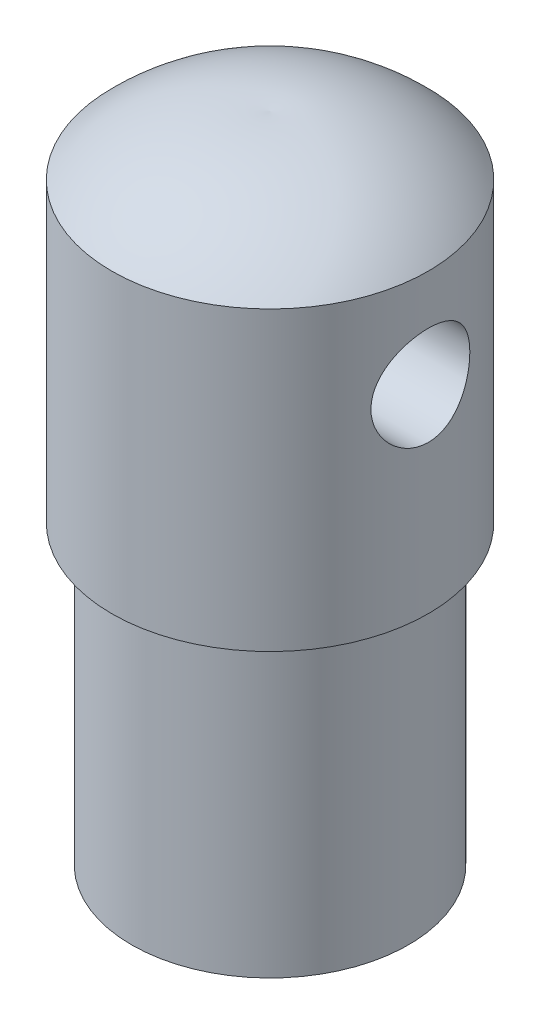
SolidWorks part; units mm, degrees
material "ABS PC"
ref_plane "Front Plane" through (0, 0, 0) normal (0, 0, 1) x (1, 0, 0)
ref_plane "Top Plane" through (0, 0, 0) normal (0, 1, 0) x (1, 0, 0)
ref_plane "Right Plane" through (0, 0, 0) normal (1, 0, 0) x (0, 0, -1)
sketch "Sketch1" plane through (0, 0, 0) normal (0, 1, 0) x (1, 0, 0)
  circle A0 centre (0, 0) radius 7
  dimension "D1" = 14
extrude "Boss-Extrude1" add sketch "Sketch1" along normal blind 15
sketch "Sketch2" plane through (0, 15, 0) normal (0, 1, 0) x (1, 0, 0)
  circle A0 centre (0, 0) radius 8
  dimension "D1" = 16
extrude "Boss-Extrude2" add sketch "Sketch2" along normal blind 15
sketch "Sketch4" plane through (0, 0, 0) normal (0, 0, 1) x (1, 0, 0)
  line L0 (8, 30) -> (-8, 30) construction
  line L1 (0, 33) -> (0, 30)
  line L2 (0, 30) -> (8, 30)
  arc A0 (8, 30) -> (0, 33) centre (0.8253, 23.0341) ccw
  dimension "D1" = 10
  dimension "D2" = 3
revolve "Revolve1" add sketch "Sketch4" angle 360 about L1
sketch "Sketch3" plane through (0, 0, 0) normal (1, 0, 0) x (0, 0, -1)
  circle A0 centre (0, 25) radius 2.5
  dimension "D1" = 5
  dimension "D2" = 25
extrude "Cut-Extrude1" cut sketch "Sketch3" against normal through all both and the other way through all
